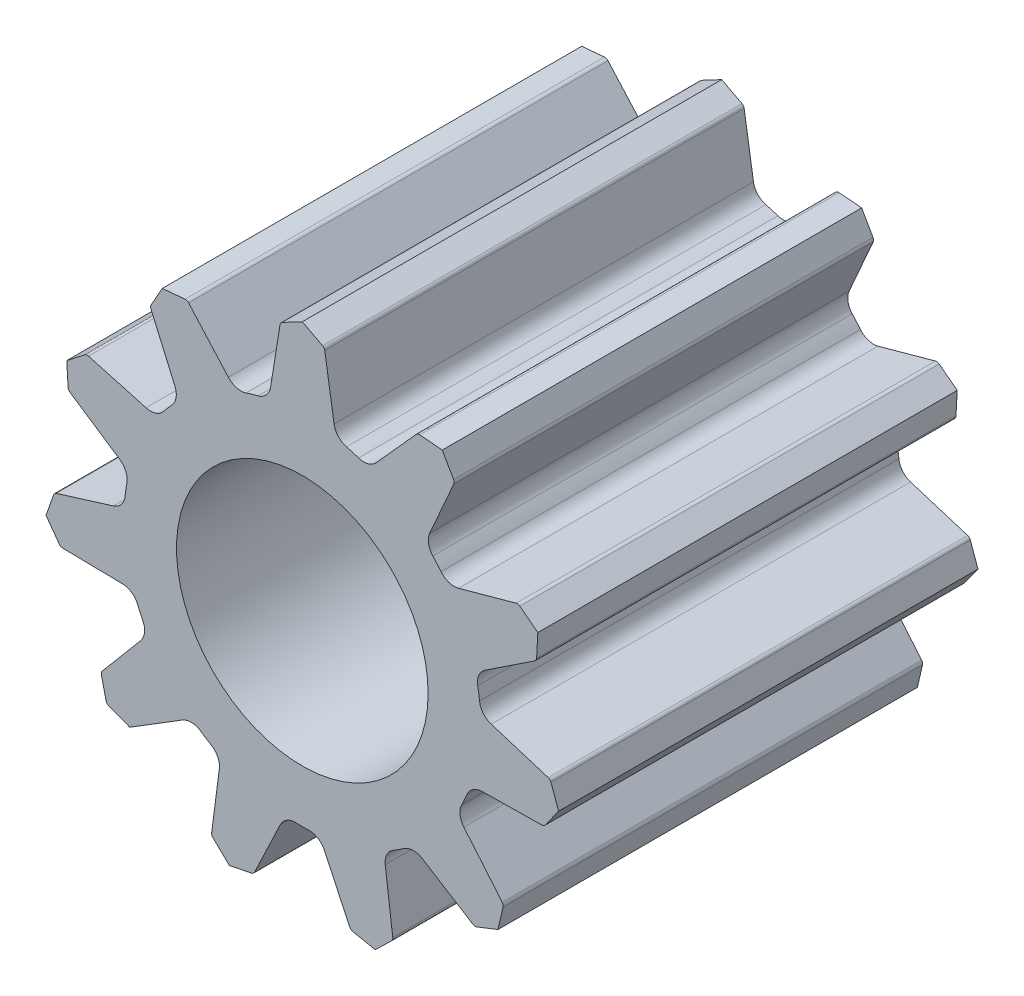
SolidWorks part; units mm, degrees
ref_plane "Front Plane" through (0, 0, 0) normal (0, 0, 1) x (1, 0, 0)
ref_plane "Top Plane" through (0, 0, 0) normal (0, 1, 0) x (1, 0, 0)
ref_plane "Right Plane" through (0, 0, 0) normal (1, 0, 0) x (0, 0, -1)
sketch "Sketch1" plane through (0, 0, 0) normal (0, 0, 1) x (1, 0, 0)
  circle A0 centre (0, 0) radius 4.25
  dimension "D1" = 8.5
extrude "Boss-Extrude1" add sketch "Sketch1" along normal blind 10 contours A0
sketch "Sketch3" plane through (0, 0, 0) normal (0, 0, 1) x (1, 0, 0)
  line L0 (0, 0) -> (0, 6.4022) construction
  line L1 (0, 6.174) -> (0.5277, 5.8974)
  line L2 (0.5277, 5.8974) -> (0.8, 4.174)
  line L3 (0.8, 4.174) -> (-0.8, 4.174)
  line L4 (-0.8, 4.174) -> (-0.5225, 5.8974)
  line L5 (-0.5225, 5.8974) -> (0, 6.174)
  circle A0 centre (0, 0) radius 4.25 construction
  dimension "D1" = 2
  dimension "D4" = 1.6
sketch "Sketch4" plane through (0, 0, 0) normal (0, 1, 0) x (1, 0, 0)
  line L0 (0, -6.6428) -> (0, 0.4527) construction
extrude "Boss-Extrude2" add sketch "Sketch3" along normal blind 10
pattern_circular "CirPattern1" count 11 over 360 about axis through (0, 0, 0) along (0, 0, 1) of "Boss-Extrude2"
sketch "Sketch5" plane through (0, 0, 0) normal (0, 0, 1) x (1, 0, 0)
  circle A0 centre (0, 0) radius 3
  dimension "D1" = 6
extrude "Cut-Extrude1" cut sketch "Sketch5" along normal blind 10
fillet "Fillet1" radius 0.4 22 edges at (2.6306, -3.338, 5) (1.9436, -3.7796, 5) (0.4084, -4.2303, 5) (-0.4084, -4.2303, 5) (-1.9436, -3.7796, 5) (-2.6306, -3.338, 5) (-3.6784, -2.1288, 5) (-4.0177, -1.3859, 5) (-4.2454, 0.1978, 5) (-4.1292, 1.0062, 5) (-3.4645, 2.4617, 5) (-2.9297, 3.0789, 5) (-1.5836, 3.9439, 5) (-0.8, 4.174, 5) (3.6784, -2.1288, 5) (4.0177, -1.3859, 5) (4.2454, 0.1978, 5) (4.1292, 1.0062, 5) (3.4645, 2.4617, 5) (2.9297, 3.0789, 5) (1.5836, 3.9439, 5) (0.8, 4.174, 5)
fillet "Fillet2" radius 0.1 22 edges at (5.1474, 2.9252, 5) (5.5837, 1.9698, 5) (5.9118, -0.3221, 5) (5.7623, -1.3617, 5) (4.7992, -3.4671, 5) (4.1114, -4.2608, 5) (2.1629, -5.5113, 5) (-1.1601, -5.8057, 5) (1.1551, -5.8072, 5) (-2.1679, -5.5099, 5) (-4.666, -4.0431, 5) (-4.8026, -3.4632, 5) (-5.763, -1.3565, 5) (-5.9125, -0.3169, 5) (-5.5815, 1.9746, 5) (-5.1453, 2.9299, 5) (-3.628, 4.6787, 5) (-2.7444, 5.2465, 5) (-0.5225, 5.8974, 5) (0.5277, 5.8974, 5) (2.7488, 5.2437, 5) (3.6323, 4.6759, 5)
